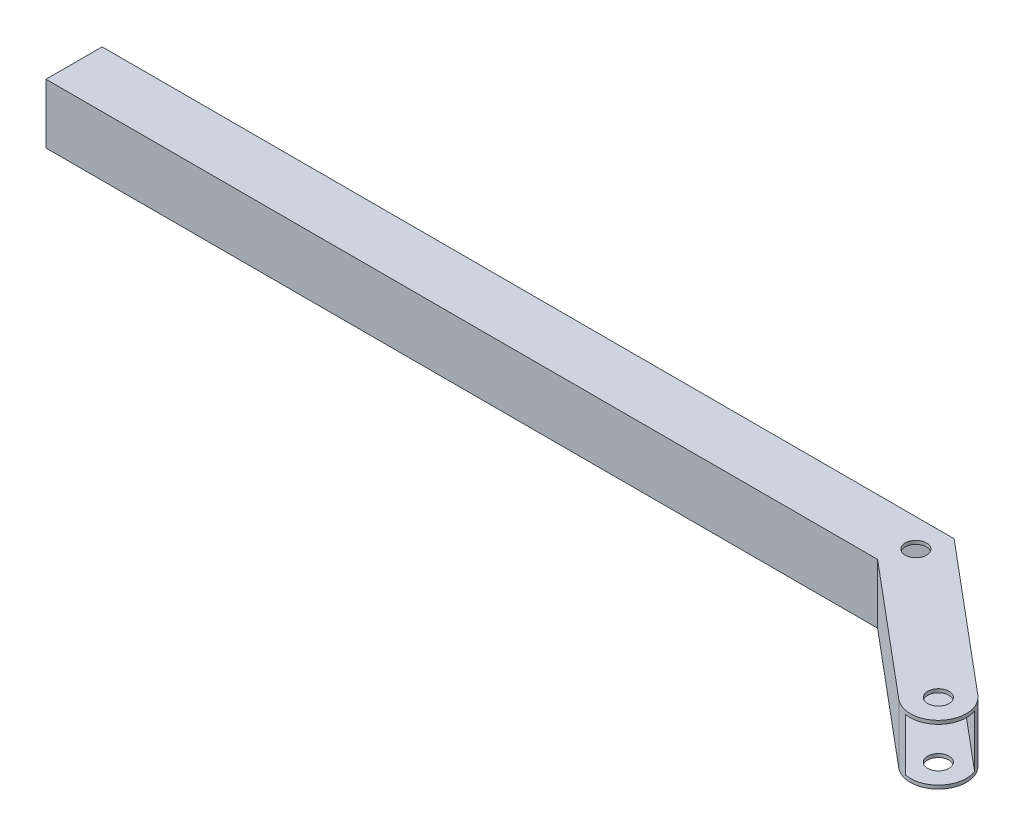
SolidWorks part; units mm, degrees
ref_plane "Front Plane" through (0, 0, 0) normal (0, 0, 1) x (1, 0, 0)
ref_plane "Top Plane" through (0, 0, 0) normal (0, 1, 0) x (1, 0, 0)
ref_plane "Right Plane" through (0, 0, 0) normal (1, 0, 0) x (0, 0, -1)
sketch "Sketch1" plane through (0, 0, 0) normal (0, 1, 0) x (1, 0, 0)
  line L0 (-385.6224, -25.4) -> (-9.2448, -25.4)
  line L1 (-9.2448, -25.4) -> (50.4511, -75.4909)
  line L2 (66.7779, -56.0334) -> (0, 0)
  line L3 (0, 0) -> (-385.6224, 0)
  line L4 (-385.6224, 0) -> (-385.6224, -25.4)
  arc A0 (50.4511, -75.4909) -> (66.7779, -56.0334) centre (58.6145, -65.7621) ccw
extrude "Boss-Extrude1" add sketch "Sketch1" along normal blind 1.5875
sketch "Sketch2" plane through (0, 1.5875, 0) normal (0, 1, 0) x (1, 0, 0)
  line L1 (-385.6224, -23.8125) -> (-385.6224, -25.4)
  line L5 (56.1815, -78.2269) -> (-8.667, -23.8125)
  line L6 (-9.2448, -25.4) -> (50.4511, -75.4909)
  line L7 (-9.2448, -25.4) -> (-385.6224, -25.4)
  line L8 (-385.6224, -23.8125) -> (-8.667, -23.8125)
  line L12 (-385.6224, 0) -> (-385.6224, -1.5875)
  line L14 (-769.9128, -1.5875) -> (-770.2244, -1.2161)
  line L15 (-770.2244, -1.2161) -> (-770.667, -1.5875)
  line L16 (-770.667, -1.5875) -> (-771.2448, -1.5875)
  line L17 (-771.2448, -1.5875) -> (-771.2448, -2.0723)
  line L18 (0, -1.5875) -> (0, -2.0723)
  line L19 (-0.5778, -1.5875) -> (0, -1.5875)
  line L20 (-1.0204, -1.2161) -> (-0.5778, -1.5875)
  line L21 (-1.3321, -1.5875) -> (-1.0204, -1.2161)
  line L22 (66.7779, -56.0334) -> (0, 0)
  line L23 (0, -2.0723) -> (70.4674, -61.2015)
  line L24 (0, 0) -> (-385.6224, 0)
  line L25 (-385.6224, -1.5875) -> (-1.3321, -1.5875)
  arc A1 (50.4511, -75.4909) -> (56.1815, -78.2269) centre (58.6145, -65.7621) ccw
  arc A3 (70.4674, -61.2015) -> (66.7779, -56.0334) centre (58.6145, -65.7621) ccw
  line M7 (-385.6224, 0) -> (-385.6224, -25.4)
  line M8 (-385.6224, -25.4) -> (-9.2448, -25.4)
  line M9 (-9.2448, -25.4) -> (50.4511, -75.4909)
  arc M10 (50.4511, -75.4909) -> (66.7779, -56.0334) centre (58.6145, -65.7621) ccw
  line M11 (66.7779, -56.0334) -> (0, 0)
  line M12 (0, 0) -> (-385.6224, 0)
extrude "Boss-Extrude2" add sketch "Sketch2" along normal blind 25.4 contours L25 L21 L20 L19 L18 L23 M7 M10 M11 M12 | L8 L5 M7 M8 M9 M10
sketch "Sketch3" plane through (0, 26.9875, 0) normal (0, 1, 0) x (1, 0, 0)
  line L2 (-385.6224, 0) -> (-385.6224, -25.4)
  line L5 (-9.2448, -25.4) -> (50.4511, -75.4909)
  line L6 (66.7779, -56.0334) -> (0, 0)
  line L7 (0, 0) -> (-385.6224, 0)
  line L8 (-385.6224, -25.4) -> (-9.2448, -25.4)
  arc A1 (50.4511, -75.4909) -> (66.7779, -56.0334) centre (58.6145, -65.7621) ccw
extrude "Boss-Extrude3" add sketch "Sketch3" against normal blind 1.5875
sketch "Sketch4" plane through (0, 26.9875, 0) normal (0, 1, 0) x (1, 0, 0)
  circle A0 centre (58.6145, -65.7621) radius 4.826
  circle A1 centre (-4.6224, -12.7) radius 4.826
extrude "Cut-Extrude1" cut sketch "Sketch4" against normal blind 55.9435
